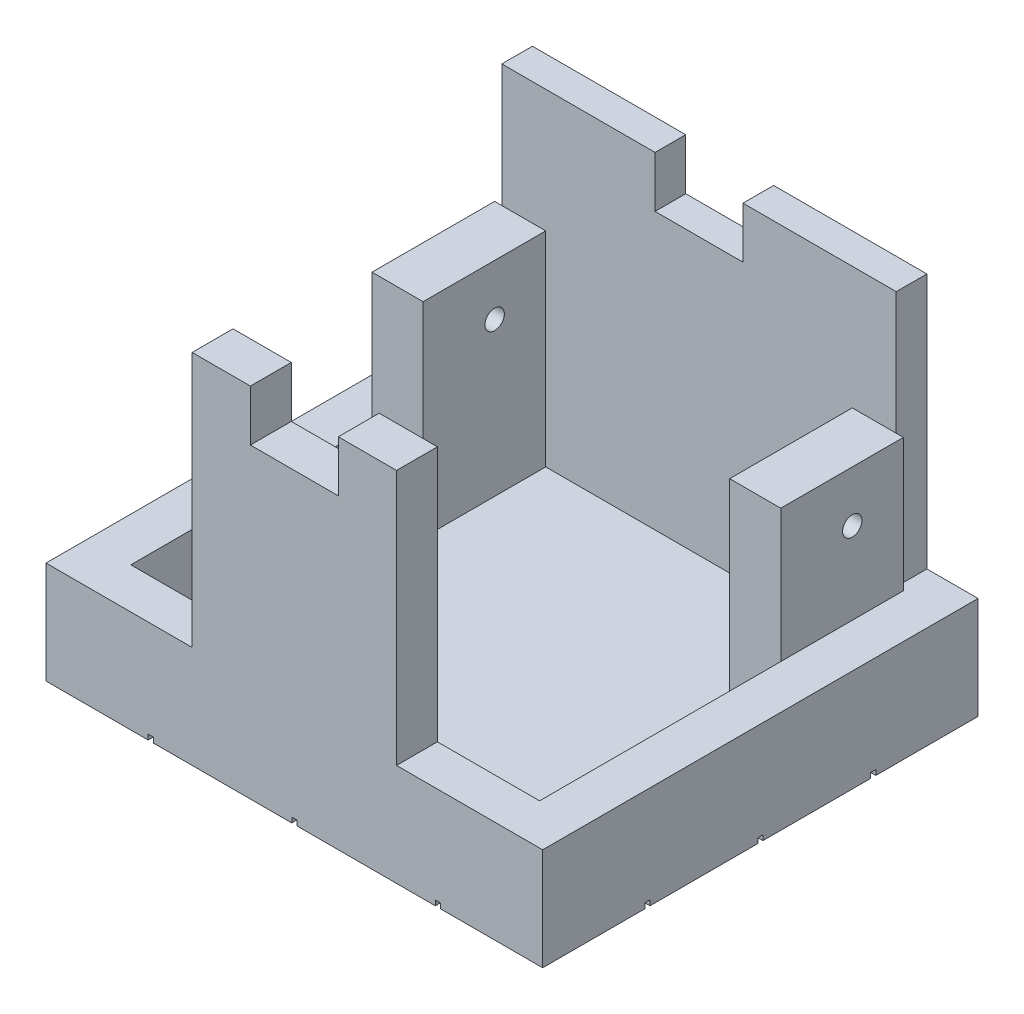
SolidWorks part; units mm, degrees
ref_plane "前视基准面" through (0, 0, 0) normal (0, 0, 1) x (1, 0, 0)
ref_plane "上视基准面" through (0, 0, 0) normal (0, 1, 0) x (1, 0, 0)
ref_plane "右视基准面" through (0, 0, 0) normal (1, 0, 0) x (0, 0, -1)
other "Configuration Table"
sketch "草图1" plane through (0, 0, 0) normal (0, 1, 0) x (1, 0, 0)
  line L1 (-24.3, 21.3) -> (24.3, 21.3)
  line L2 (-24.3, 21.3) -> (-24.3, -21.3)
  line L3 (-24.3, -21.3) -> (24.3, -21.3)
  line L4 (24.3, 21.3) -> (24.3, -21.3)
  line L5 (-24.3, 21.3) -> (24.3, -21.3) construction
  line L6 (-24.3, -21.3) -> (24.3, 21.3) construction
  point P0 (0, 0)
  dimension "D1" = 48.6
  dimension "D2" = 42.6
extrude "凸台-拉伸1" add sketch "草图1" along normal blind 3
sketch "草图2" plane through (0, 3, 0) normal (0, 1, 0) x (1, 0, 0)
  line L0 (-24.3, 21.3) -> (-24.3, -21.3)
  line L1 (-24.3, -21.3) -> (24.3, -21.3) construction
  line L2 (-24.3, -21.3) -> (24.3, -21.3)
  line L3 (24.3, -21.3) -> (24.3, 21.3)
  line L4 (24.3, -21.3) -> (24.3, 21.3) construction
  line L5 (24.3, 21.3) -> (-24.3, 21.3) construction
  line L7 (20, 18.3) -> (20, -17.3)
  line L8 (20, -17.3) -> (-20, -17.3)
  line L9 (-20, -17.3) -> (-20, 18.3)
  line L11 (-24.3, 21.3) -> (24.3, 21.3)
  line L12 (-20, 18.3) -> (20, 18.3)
  dimension "D1" = 4
  dimension "D2" = 4.3
  dimension "D3" = 4.3
  dimension "D4" = 3
extrude "凸台-拉伸2" add sketch "草图2" along normal blind 7
sketch "草图3" plane through (0, 10, 0) normal (0, 1, 0) x (1, 0, 0)
  line L0 (0, 0) -> (0, -50000) construction
  line L1 (-4.4378, -19.3) -> (49995.5622, -19.3) construction
  line L2 (-24.3, -21.3) -> (24.3, -21.3) construction
  line L4 (-16.1356, 19.8) -> (49983.8644, 19.8) construction
  line L5 (-10, -17.3) -> (10, -17.3)
  line L6 (-10, -17.3) -> (-10, -21.3)
  line L7 (-10, -21.3) -> (10, -21.3)
  line L8 (10, -17.3) -> (10, -21.3)
  line L9 (-10, -17.3) -> (10, -21.3) construction
  line L10 (-10, -21.3) -> (10, -17.3) construction
  line L11 (20, 18.3) -> (-20, 18.3) construction
  line L13 (24.3, 21.3) -> (-24.3, 21.3) construction
  line L14 (-19.3, 21.3) -> (19.3, 21.3)
  line L15 (-19.3, 21.3) -> (-19.3, 18.3)
  line L16 (-19.3, 18.3) -> (19.3, 18.3)
  line L17 (19.3, 21.3) -> (19.3, 18.3)
  line L18 (-19.3, 21.3) -> (19.3, 18.3) construction
  line L19 (-19.3, 18.3) -> (19.3, 21.3) construction
  point P7 (0, -19.3)
  point P16 (0, 19.8)
  dimension "D1" = 2
  dimension "D2" = 20
  dimension "D3" = 1.5
  dimension "D4" = 38.6
extrude "凸台-拉伸3" add sketch "草图3" along normal blind 20
sketch "草图6" plane through (0, 30, 0) normal (0, 1, 0) x (1, 0, 0)
  line L0 (20, 18.3) -> (-20, 18.3) construction
  line L1 (-19.3, 21.3) -> (-4.3, 21.3)
  line L2 (-19.3, 21.3) -> (-19.3, 18.3)
  line L3 (-19.3, 18.3) -> (-4.3, 18.3)
  line L4 (-4.3, 21.3) -> (-4.3, 18.3)
  line L5 (-10, -21.3) -> (10, -21.3) construction
  line L6 (19.3, 21.3) -> (4.3, 21.3)
  line L7 (19.3, 21.3) -> (19.3, 18.3)
  line L8 (19.3, 18.3) -> (4.3, 18.3)
  line L9 (4.3, 21.3) -> (4.3, 18.3)
  line L10 (-10, -17.3) -> (-4.3, -17.3)
  line L11 (-10, -17.3) -> (-10, -21.3)
  line L12 (-10, -21.3) -> (-4.3, -21.3)
  line L13 (-4.3, -17.3) -> (-4.3, -21.3)
  line L15 (10, -17.3) -> (4.3, -17.3)
  line L16 (10, -17.3) -> (10, -21.3)
  line L17 (10, -21.3) -> (4.3, -21.3)
  line L18 (4.3, -17.3) -> (4.3, -21.3)
  dimension "D1" = 15
  dimension "D2" = 15
  dimension "D3" = 5.7
  dimension "D4" = 5.7
extrude "凸台-拉伸4" add sketch "草图6" along normal blind 5
sketch "草图7" plane through (0, 3, 0) normal (0, 1, 0) x (1, 0, 0)
  line L0 (24.3, 21.3) -> (19.3, 21.3) construction
  line L1 (20, 18.3) -> (15, 18.3)
  line L2 (20, 18.3) -> (20, 6.3)
  line L3 (20, 6.3) -> (15, 6.3)
  line L4 (15, 18.3) -> (15, 6.3)
  line L5 (-20, 18.3) -> (-15, 18.3)
  line L6 (-20, 18.3) -> (-20, 6.3)
  line L7 (-20, 6.3) -> (-15, 6.3)
  line L8 (-15, 18.3) -> (-15, 6.3)
  line L9 (-4.3, 21.3) -> (-19.3, 21.3) construction
  dimension "D1" = 15
  dimension "D2" = 15
  dimension "D3" = 5
  dimension "D4" = 5
extrude "凸台-拉伸5" add sketch "草图7" along normal blind 20
sketch "草图8" plane through (24.3, 0, 0) normal (1, 0, 0) x (0, 0, -1)
  line L0 (-21.3, 0) -> (21.3, 0) construction
  line L1 (21.3, 35) -> (21.3, 10) construction
  circle A0 centre (13.3, 18) radius 0.95
  dimension "D3" = 1.9
  dimension "D1" = 18
  dimension "D2" = 8
extrude "切除-拉伸1" cut sketch "草图8" against normal through all
sketch "草图9" plane through (0, 0, 0) normal (0, -1, 0) x (1, 0, 0)
  line L0 (-24.3, -21.3) -> (-24.3, 21.3) construction
  line L1 (-24.3, 11.3) -> (24.3, 11.3)
  line L2 (-24.3, 11.3) -> (-24.3, 10.8)
  line L3 (-24.3, 10.8) -> (24.3, 10.8)
  line L4 (24.3, 11.3) -> (24.3, 10.8)
  line L5 (24.3, 21.3) -> (24.3, -21.3) construction
  line L6 (-24.3, 21.3) -> (24.3, 21.3) construction
  line L7 (-24.3, -10.8) -> (24.3, -10.8)
  line L8 (-24.3, -10.8) -> (-24.3, -11.3)
  line L9 (-24.3, -11.3) -> (24.3, -11.3)
  line L10 (24.3, -10.8) -> (24.3, -11.3)
  line L11 (24.3, -21.3) -> (-24.3, -21.3) construction
  line L13 (-24.3, 0.25) -> (24.3, 0.25)
  line L14 (-24.3, 0.25) -> (-24.3, -0.25)
  line L15 (-24.3, -0.25) -> (24.3, -0.25)
  line L16 (24.3, 0.25) -> (24.3, -0.25)
  line L17 (-24.3, 0.25) -> (24.3, -0.25) construction
  line L18 (-24.3, -0.25) -> (24.3, 0.25) construction
  point P16 (0, 0)
  dimension "D1" = 0.5
  dimension "D2" = 0.5
  dimension "D3" = 10
  dimension "D4" = 10
  dimension "D5" = 0.5
extrude "切除-拉伸2" cut sketch "草图9" against normal blind 0.5
sketch "草图10" plane through (0, 0, 0) normal (0, -1, 0) x (1, 0, 0)
  line L0 (-24.3, 21.3) -> (24.3, 21.3) construction
  line L1 (0.25, -21.3) -> (-0.25, -21.3)
  line L2 (0.25, -21.3) -> (0.25, 21.3)
  line L3 (0.25, 21.3) -> (-0.25, 21.3)
  line L4 (-0.25, -21.3) -> (-0.25, 21.3)
  line L5 (0.25, -21.3) -> (-0.25, 21.3) construction
  line L6 (0.25, 21.3) -> (-0.25, -21.3) construction
  line L7 (24.3, -21.3) -> (-24.3, -21.3) construction
  line L8 (-14.3, 21.3) -> (-13.8, 21.3)
  line L9 (-14.3, 21.3) -> (-14.3, -21.3)
  line L10 (-14.3, -21.3) -> (-13.8, -21.3)
  line L11 (-13.8, 21.3) -> (-13.8, -21.3)
  line L12 (-24.3, 11.3) -> (-24.3, 21.3) construction
  line L13 (13.8, 21.3) -> (14.3, 21.3)
  line L14 (13.8, 21.3) -> (13.8, -21.3)
  line L15 (13.8, -21.3) -> (14.3, -21.3)
  line L16 (14.3, 21.3) -> (14.3, -21.3)
  line L17 (24.3, 21.3) -> (24.3, 11.3) construction
  point P0 (0, 0)
  dimension "D1" = 0.5
  dimension "D2" = 0.5
  dimension "D3" = 0.5
  dimension "D4" = 10
  dimension "D5" = 10
extrude "切除-拉伸3" cut sketch "草图10" against normal blind 0.5
